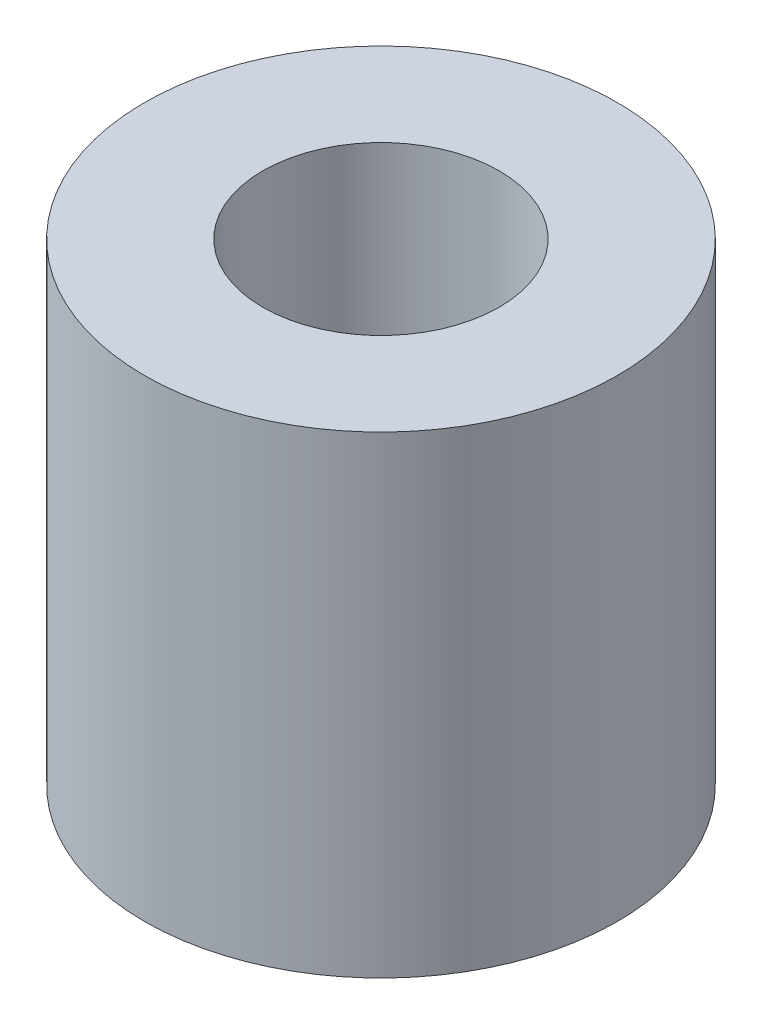
SolidWorks part; units mm, degrees
ref_plane "Front Plane" through (0, 0, 0) normal (0, 0, 1) x (1, 0, 0)
ref_plane "Top Plane" through (0, 0, 0) normal (0, 1, 0) x (1, 0, 0)
ref_plane "Right Plane" through (0, 0, 0) normal (1, 0, 0) x (0, 0, -1)
sketch "Sketch1" plane through (0, 0, 0) normal (0, 1, 0) x (1, 0, 0)
  circle A0 centre (0, 0) radius 2
  circle A1 centre (0, 0) radius 1
  dimension "D1" = 4
  dimension "D2" = 2
extrude "Boss-Extrude1" add sketch "Sketch1" along normal blind 4
